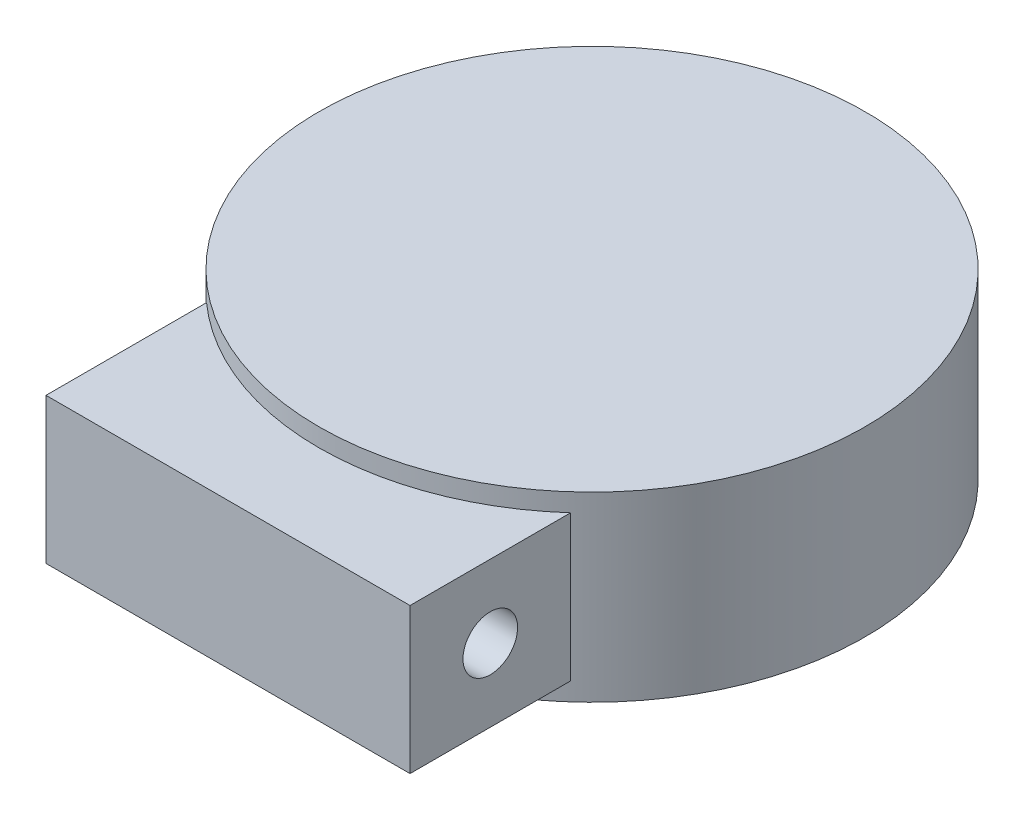
SolidWorks part; units mm, degrees
ref_plane "Front Plane" through (0, 0, 0) normal (0, 0, 1) x (1, 0, 0)
ref_plane "Top Plane" through (0, 0, 0) normal (0, 1, 0) x (1, 0, 0)
ref_plane "Right Plane" through (0, 0, 0) normal (1, 0, 0) x (0, 0, -1)
sketch "Sketch1" plane through (0, 0, 0) normal (0, 1, 0) x (1, 0, 0)
  circle A0 centre (0, 0) radius 38.1
  dimension "D1" = 76.2
extrude "Boss-Extrude1" add sketch "Sketch1" along normal blind 25.4
sketch "Sketch2" plane through (0, 0, 0) normal (0, 0, 1) x (1, 0, 0)
  line L0 (38.1, 25.4) -> (-38.1, 25.4) construction
  line L1 (25.4, 22.86) -> (-25.4, 22.86)
  line L2 (25.4, 22.86) -> (25.4, 2.54)
  line L3 (25.4, 2.54) -> (-25.4, 2.54)
  line L4 (-25.4, 22.86) -> (-25.4, 2.54)
  line L5 (25.4, 22.86) -> (-25.4, 2.54) construction
  line L6 (25.4, 2.54) -> (-25.4, 22.86) construction
  line L7 (-38.1, 0) -> (38.1, 0) construction
  line L8 (-38.1, 25.4) -> (-38.1, 0) construction
  line L9 (38.1, 0) -> (38.1, 25.4) construction
  point P0 (0, 12.7)
  dimension "D1" = 2.54
  dimension "D2" = 2.54
  dimension "D3" = 12.7
  dimension "D4" = 12.7
extrude "Boss-Extrude2" add sketch "Sketch2" along normal blind 50.8
sketch "Sketch3" plane through (-25.4, 0, 0) normal (-1, 0, 0) x (0, 0, 1)
  line L0 (39.599, 22.86) -> (39.599, 2.54) construction
  line L1 (50.8, 22.86) -> (28.3981, 22.86) construction
  line L2 (50.8, 2.54) -> (28.3981, 2.54) construction
  circle A0 centre (39.599, 12.7) radius 3.81
  dimension "D1" = 7.62
extrude "Cut-Extrude1" cut sketch "Sketch3" against normal up to next
